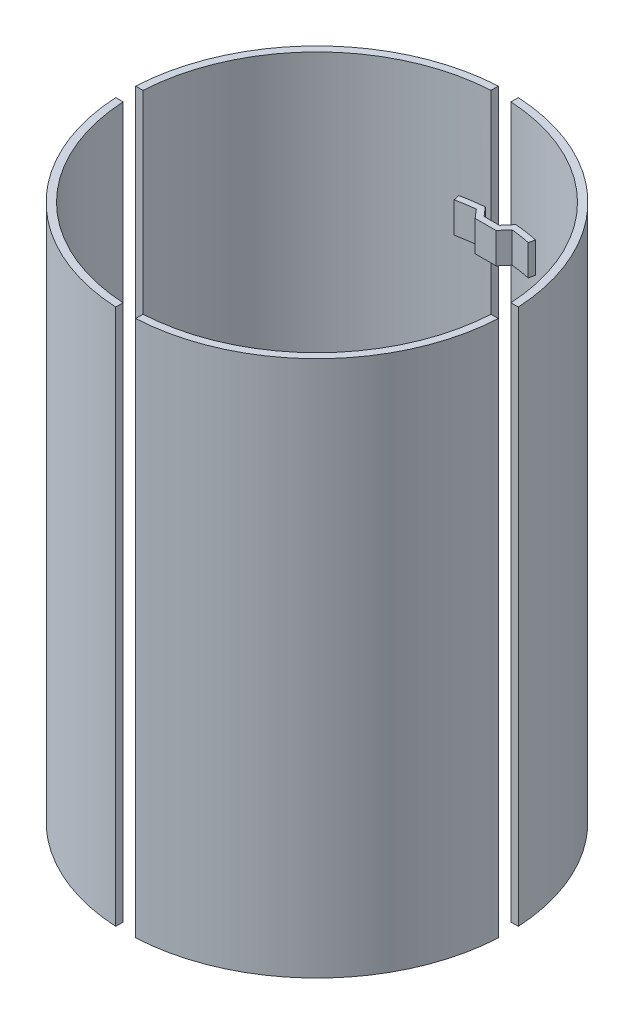
SolidWorks part; units mm, degrees
ref_plane "Front Plane" through (0, 0, 0) normal (0, 0, 1) x (1, 0, 0)
ref_plane "Top Plane" through (0, 0, 0) normal (0, 1, 0) x (1, 0, 0)
ref_plane "Right Plane" through (0, 0, 0) normal (1, 0, 0) x (0, 0, -1)
sketch "Sketch1" plane through (0, 0, 0) normal (0, 1, 0) x (1, 0, 0)
  circle A0 centre (0, 0) radius 62.5
  circle A1 centre (0, 0) radius 60.1
  dimension "D1" = 2.4
  dimension "D2" = 125
extrude "Boss-Extrude1" add sketch "Sketch1" along normal mid plane 175
sketch "Sketch2" plane through (0, 87.5, 0) normal (0, 1, 0) x (1, 0, 0)
  line L0 (0, 0) -> (0, 76.4001) construction
  line L2 (-3.25, 62.5) -> (3.25, 62.5)
  line L3 (-3.25, 62.5) -> (-3.25, 60.0121)
  line L4 (-3.25, 60.0121) -> (3.25, 60.0121)
  line L5 (3.25, 62.5) -> (3.25, 60.0121)
  circle A0 centre (0, 0) radius 62.5 construction
  circle A1 centre (0, 0) radius 60.1 construction
  point P9 (0, 0)
  dimension "D1" = 6.5
extrude "Cut-Extrude1" cut sketch "Sketch2" against normal through all
pattern_circular "CirPattern1" count 4 over 360 about axis through (0, 0, 0) along (0, 1, 0) of "Cut-Extrude1"
ref_plane "Plane1" through (0, 43.75, 0) normal (0, 1, 0) x (1, 0, 0)
sketch "Sketch3" plane through (0, 43.75, 0) normal (0, 1, 0) x (1, 0, 0)
  line L0 (-5, 59.8917) -> (-2.5, 57)
  line L1 (-2.5, 57) -> (2.5, 57)
  line L2 (2.5, 57) -> (5, 59.8917)
  line L3 (0, 0) -> (0, 63) construction
  line L4 (-3.25, 60.0121) -> (3.25, 60.0121) construction
  arc A0 (60.0121, 3.25) -> (3.25, 60.0121) centre (0, 0) ccw construction
  arc A1 (-3.25, 60.0121) -> (-60.0121, 3.25) centre (0, 0) ccw construction
  arc A2 (12.5, 58.7857) -> (5, 59.8917) centre (0, 0) ccw
  arc A3 (-5, 59.8917) -> (-12.5, 58.7857) centre (0, 0) ccw
  point P15 (0, 0)
  dimension "D5" = 10
  dimension "D1" = 25
  dimension "D2" = 6
  dimension "D3" = 5
  dimension "D4" = 63
extrude "Extrude-Thin1" add sketch "Sketch3" along normal blind 10 thin
